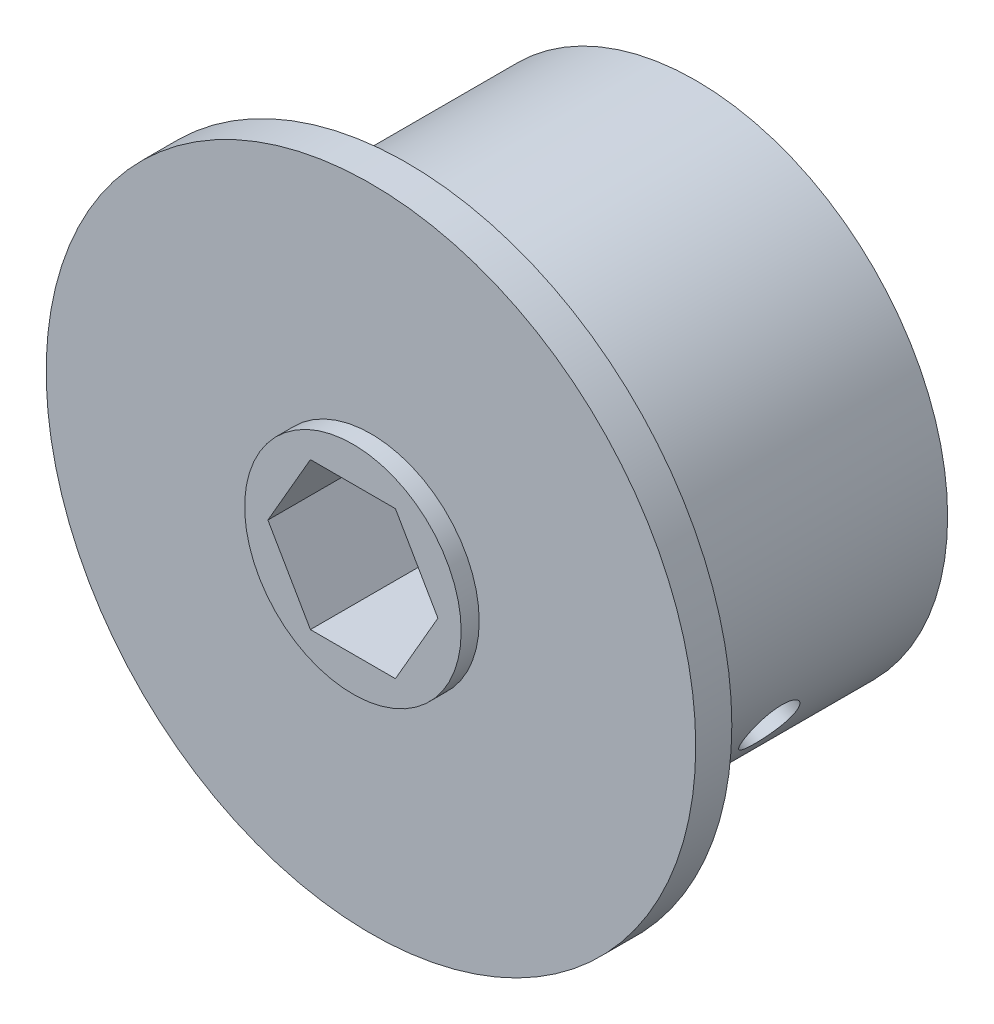
SolidWorks part; units mm, degrees
material "PET"
ref_plane "Front Plane" through (0, 0, 0) normal (0, 0, 1) x (1, 0, 0)
ref_plane "Top Plane" through (0, 0, 0) normal (0, 1, 0) x (1, 0, 0)
ref_plane "Right Plane" through (0, 0, 0) normal (1, 0, 0) x (0, 0, -1)
sketch "Sketch1" plane through (0, 0, 0) normal (0, 0, 1) x (1, 0, 0)
  line L1 (7.479, 0) -> (3.7395, 6.477)
  line L2 (3.7395, 6.477) -> (-3.7395, 6.477)
  line L3 (-3.7395, 6.477) -> (-7.479, 0)
  line L4 (-7.479, 0) -> (-3.7395, -6.477)
  line L5 (-3.7395, -6.477) -> (3.7395, -6.477)
  line L6 (3.7395, -6.477) -> (7.479, 0)
  circle A0 centre (0, 0) radius 22.1615
  circle A1 centre (0, 0) radius 6.477 construction
  dimension "D1" = 44.323
  dimension "D2" = 12.954
extrude "Boss-Extrude1" add sketch "Sketch1" along normal blind 12.7
sketch "Sketch2" plane through (0, 0, 12.7) normal (0, 0, 1) x (1, 0, 0)
  line L0 (3.7395, -6.477) -> (7.479, 0) construction
  line L1 (7.479, 0) -> (3.7395, 6.477)
  line L2 (3.7395, 6.477) -> (-3.7395, 6.477)
  line L3 (-3.7395, 6.477) -> (-7.479, 0)
  line L4 (-7.479, 0) -> (-3.7395, -6.477)
  line L5 (-3.7395, -6.477) -> (3.7395, -6.477)
  line L6 (3.7395, -6.477) -> (7.479, 0)
  circle A0 centre (0, 0) radius 28.575
  circle A1 centre (0, 0) radius 6.477 construction
  dimension "D1" = 57.15
extrude "Boss-Extrude2" add sketch "Sketch2" along normal blind 3.175
sketch "Sketch3" plane through (0, 0, 0) normal (0, 0, -1) x (-1, 0, 0)
  circle A0 centre (0, 0) radius 22.1615
  dimension "D1" = 44.323
extrude "Boss-Extrude3" add sketch "Sketch3" along normal blind 12.7
sketch "Sketch5" plane through (0, 0, 15.875) normal (0, 0, 1) x (1, 0, 0)
  line L0 (3.7395, -6.477) -> (7.479, 0) construction
  line L1 (7.479, 0) -> (3.7395, 6.477)
  line L2 (3.7395, 6.477) -> (-3.7395, 6.477)
  line L3 (-3.7395, 6.477) -> (-7.479, 0)
  line L4 (-7.479, 0) -> (-3.7395, -6.477)
  line L5 (-3.7395, -6.477) -> (3.7395, -6.477)
  line L6 (3.7395, -6.477) -> (7.479, 0)
  line L7 (3.7395, -6.477) -> (7.479, 0) construction
  circle A0 centre (0, 0) radius 9.525
  circle A1 centre (0, 0) radius 6.477 construction
  dimension "D1" = 19.05
extrude "Boss-Extrude4" add sketch "Sketch5" along normal blind 1.5875
sketch "Sketch6" plane through (0, 0, 0) normal (0, 0, 1) x (1, 0, 0)
  circle A0 centre (0, 0) radius 3.175
  dimension "D1" = 6.35
extrude "Cut-Extrude1" cut sketch "Sketch6" against normal blind 17.78
ref_point "Point5"
sketch "Sketch8" plane through (5.6092, -3.2385, 0) normal (-0.866, 0.5, 0) x (0, 0, 1)
  circle A0 centre (0, 0) radius 2.413
extrude "Cut-Extrude2" cut sketch "Sketch8" against normal blind 21.336 contours A0
sketch "Sketch9" plane through (-5.6092, 3.2385, 0) normal (0.866, -0.5, 0) x (0, 0, -1)
  circle A0 centre (0, 0) radius 2.413
extrude "Cut-Extrude3" cut sketch "Sketch9" against normal blind 22.86
sketch "Sketch10" plane through (-5.6092, 3.2385, 0) normal (-0.866, 0.5, 0) x (0, 0, 1)
  circle A0 centre (0, 0) radius 2.413
extrude "Boss-Extrude6" add sketch "Sketch10" along normal blind 6.35
sketch "Sketch11" plane through (5.6092, -3.2385, 0) normal (0.866, -0.5, 0) x (0, 0, -1)
  circle A0 centre (0, 0) radius 2.413
extrude "Boss-Extrude7" add sketch "Sketch11" along normal blind 6.35
